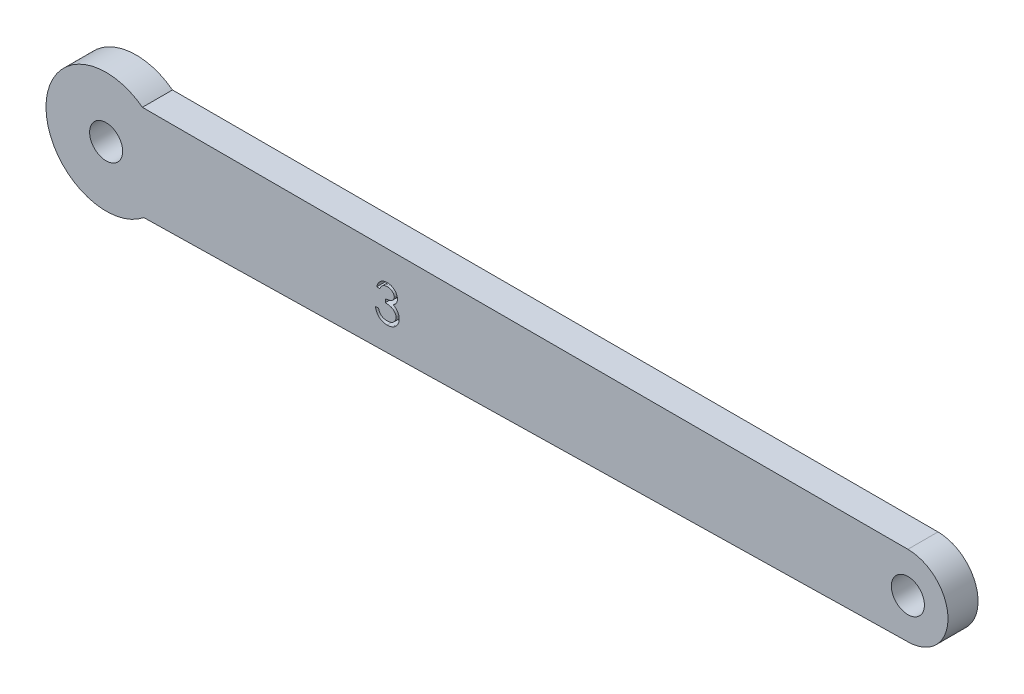
SolidWorks part; units mm, degrees
ref_plane "前视基准面" through (0, 0, 0) normal (0, 0, 1) x (1, 0, 0)
ref_plane "上视基准面" through (0, 0, 0) normal (0, 1, 0) x (1, 0, 0)
ref_plane "右视基准面" through (0, 0, 0) normal (1, 0, 0) x (0, 0, -1)
ref_plane "基准面4" through (0, 0, 3) normal (0, 0, 1) x (1, 0, 0)
sketch "草图1" plane through (0, 0, 3) normal (0, 0, 1) x (1, 0, 0)
  line L0 (23.778, 8.4676) -> (-52.5964, 8.4676)
  line L1 (-52.4516, -0.9904) -> (23.8566, 0.4686)
  arc A0 (-52.5964, 8.4676) -> (-52.4516, -0.9904) centre (-56.2156, 3.6821) ccw
  arc A1 (23.8566, 0.4686) -> (23.778, 8.4676) centre (23.778, 4.4677) ccw
extrude "凸台-拉伸1" add sketch "草图1" against normal blind 3
sketch "草图2" plane through (0, 0, 3) normal (0, 0, 1) x (1, 0, 0)
  circle A0 centre (23.778, 4.4676) radius 1.35
extrude "切除-拉伸1" cut sketch "草图2" against normal blind 2.4444
sketch "草图3" plane through (0, 0, 0) normal (0, 0, -1) x (-1, 0, 0)
  circle A0 centre (-23.778, 4.4678) radius 1.35
extrude "切除-拉伸2" cut sketch "草图3" against normal blind 0.5556
hole_wizard "Ø2.7 (2.7) 直径孔1" positions "草图5" profile "草图4" hole size "Ø2.7" standard "ANSI Metric"
sketch "草图5" plane through (0, 0, 3) normal (0, 0, 1) x (1, 0, 0)
  point P0 (-56.2156, 3.6821)
sketch "草图4" plane through (-56.2156, 3.6821, 3) normal (1, 0, 0) x (0, -1, 0)
  line L0 (0, 0) -> (0, 3)
  line L1 (0, 3) -> (1.35, 3)
  line L2 (1.35, 3) -> (1.35, 0)
  line L5 (1.35, 0) -> (0, 0)
  line L11 (0, -6.35) -> (0, 107.95) construction
  dimension "通孔孔直径" = 2.7
  dimension "通孔孔深度" = 3
sketch "草图6" plane through (0, 0, 3) normal (0, 0, 1) x (1, 0, 0)
  circle A0 centre (-56.2156, 3.6821) radius 1.65
  circle A1 centre (23.778, 4.4678) radius 1.65
  dimension "D1" = 3.3
extrude "切除-拉伸3" cut sketch "草图6" against normal through all
sketch "草图7" plane through (0, 0, 3) normal (0, 0, 1) x (1, 0, 0)
  text T0 "3"
extrude "切除-拉伸4" cut sketch "草图7" against normal blind 1
